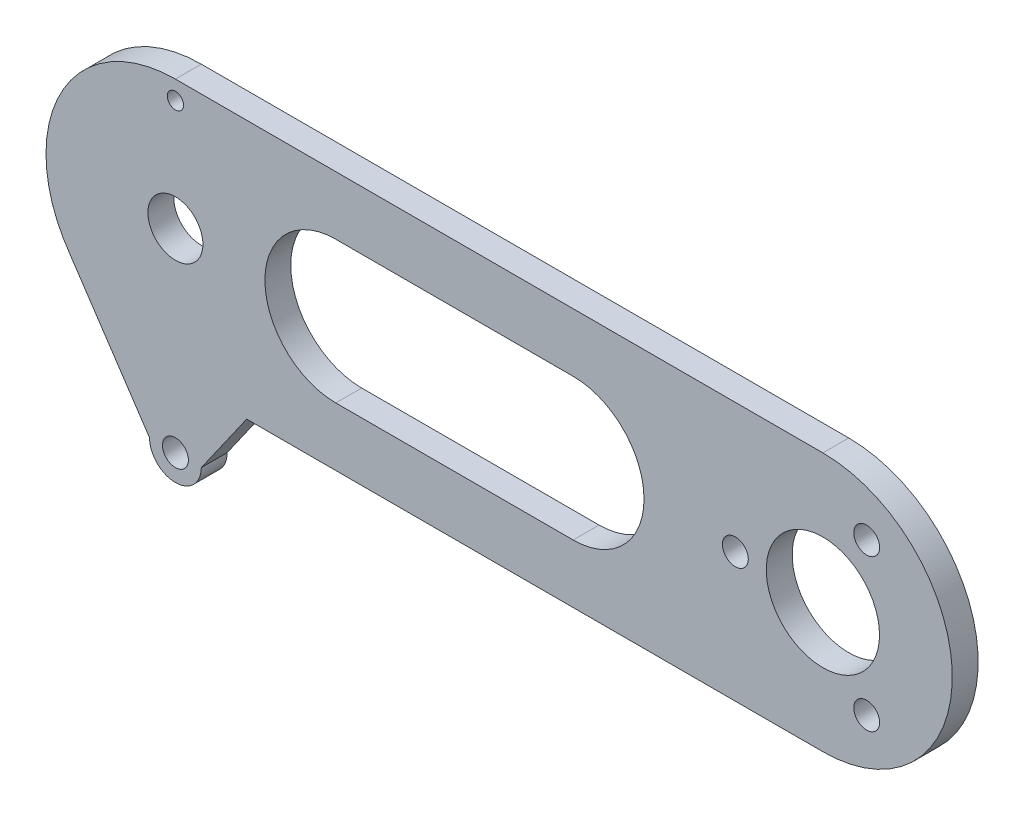
SolidWorks part; units mm, degrees
other "标注1"
sketch "草图6" plane through (-21, -34, 4) normal (0, 0, 1) x (1, 0, 0)
other "标注2"
sketch "草图7" plane through (-21, -34, 4) normal (0, 0, 1) x (1, 0, 0)
ref_plane "前视基准面" through (0, 0, 0) normal (0, 0, 1) x (1, 0, 0)
ref_plane "上视基准面" through (0, 0, 0) normal (0, 1, 0) x (1, 0, 0)
ref_plane "右视基准面" through (0, 0, 0) normal (1, 0, 0) x (0, 0, -1)
sketch "草图1" plane through (0, 0, 0) normal (0, 0, 1) x (1, 0, 0)
  line L0 (-1, 20) -> (99.0643, 20)
  line L7 (23.7835, 0) -> (60.4665, 0) construction
  line L12 (23.7835, 10.9539) -> (60.4665, 10.9539)
  line L13 (23.7835, -10.9539) -> (60.4665, -10.9539)
  line L19 (-1, 0) -> (-1, -30) construction
  line L20 (-5, -30) -> (-17.2082, -11.7173)
  line L59 (0, 32.5) -> (-18, 32.5) construction
  line L61 (3, -30) -> (10.0145, -20)
  line L62 (10.0145, -20) -> (99.0643, -20)
  line L63 (-1, 20) -> (-1, 17.12) construction
  circle A0 centre (-1, 0) radius 4.25
  arc A9 (-1, 20) -> (-1, -20) centre (-1, 0) ccw construction
  circle A13 centre (99.0643, 0) radius 8.75
  circle A18 centre (99.0643, 0) radius 13.53 construction
  arc A22 (99.0643, 20) -> (99.0643, -20) centre (99.0643, 0) cw
  arc A25 (23.7835, 10.9539) -> (23.7835, -10.9539) centre (23.7835, 0) ccw
  arc A26 (60.4665, -10.9539) -> (60.4665, 10.9539) centre (60.4665, 0) ccw
  circle A27 centre (85.5343, 0) radius 2
  circle A28 centre (105.8293, 11.7173) radius 2
  circle A29 centre (105.8293, -11.7173) radius 2
  circle A30 centre (-1, -30) radius 2
  circle A31 centre (-1, -30) radius 4 construction
  arc A32 (-17.2082, -11.7173) -> (-1, 20) centre (-1, 0) cw
  arc A33 (-5, -30) -> (3, -30) centre (-1, -30) ccw
  circle A34 centre (-1, 17.12) radius 1.25
  point P14 (42.125, 0)
  dimension "D1" = 8.5
  dimension "D2" = 3
  dimension "D3" = 17.5
extrude "凸台-拉伸1" add sketch "草图1" along normal blind 4
sketch "草图4" plane through (0, 0, 4) normal (0, 0, 1) x (1, 0, 0)
  circle A0 centre (-1, 0) radius 5
sketch "草图5" plane through (0, 0, 0) normal (0, 0, -1) x (-1, 0, 0)
  circle A0 centre (1, 0) radius 5
